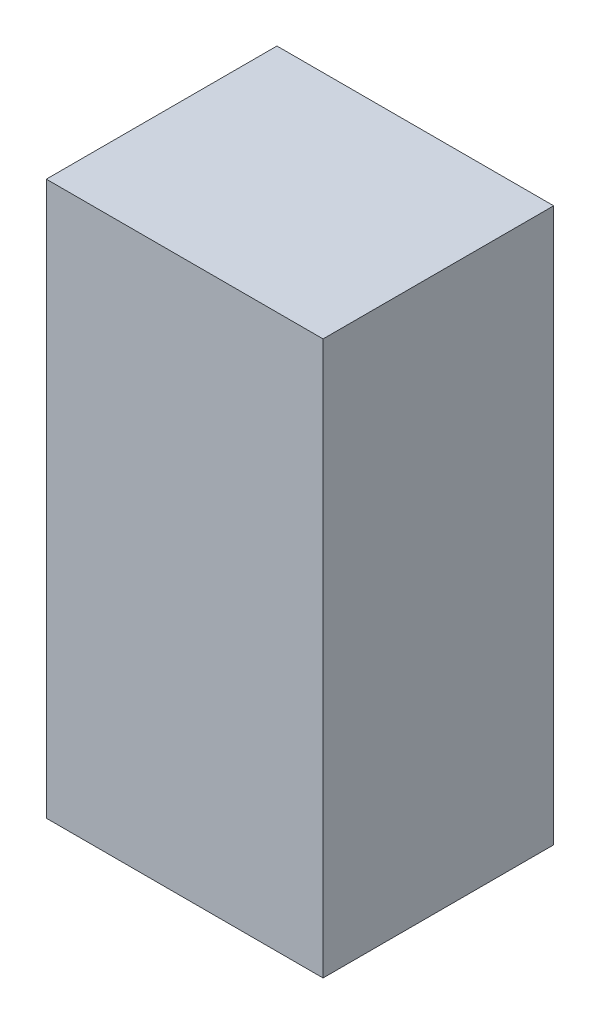
SolidWorks part; units mm, degrees
ref_plane "Front Plane" through (0, 0, 0) normal (0, 0, 1) x (1, 0, 0)
ref_plane "Top Plane" through (0, 0, 0) normal (0, 1, 0) x (1, 0, 0)
ref_plane "Right Plane" through (0, 0, 0) normal (1, 0, 0) x (0, 0, -1)
sketch "Sketch1" plane through (0, 0, 0) normal (0, 0, 1) x (1, 0, 0)
  line L1 (-600, -1200) -> (600, -1200)
  line L2 (-600, -1200) -> (-600, 1200)
  line L3 (-600, 1200) -> (600, 1200)
  line L4 (600, -1200) -> (600, 1200)
extrude "Boss-Extrude1" add sketch "Sketch1" along normal blind 1000 from offset 500
